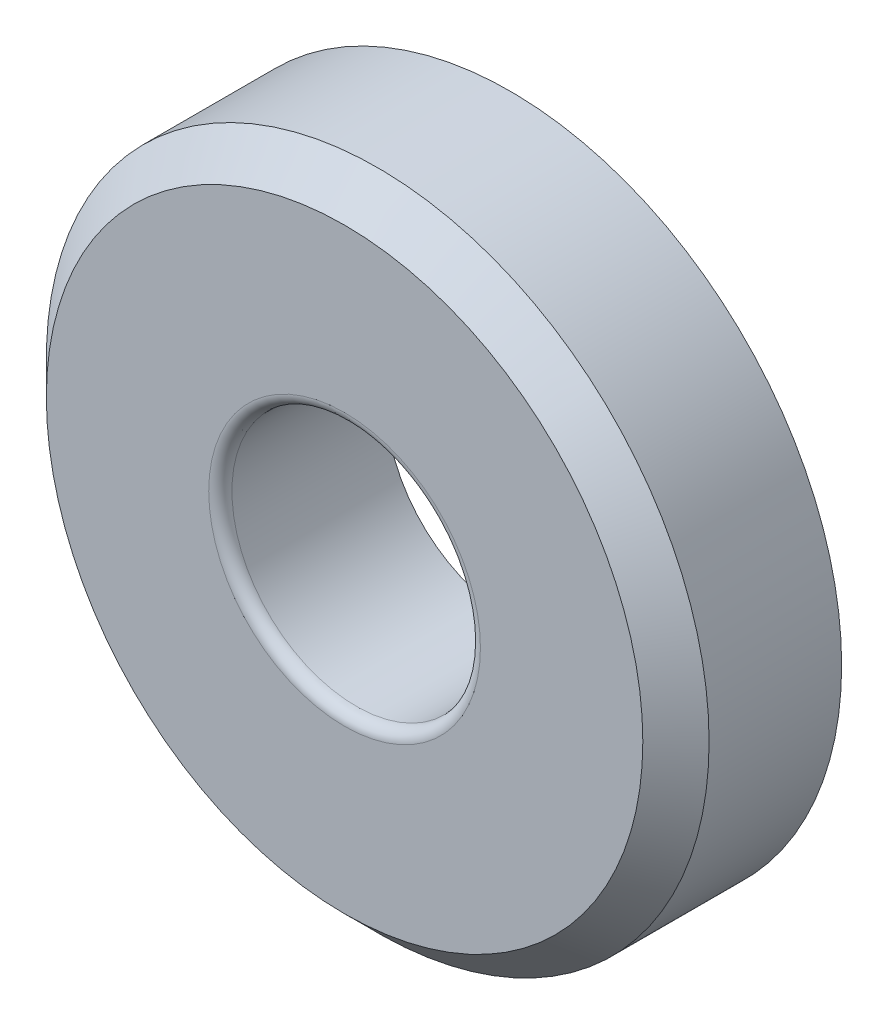
SolidWorks part; units mm, degrees
ref_plane "Front Plane" through (0, 0, 0) normal (0, 0, 1) x (1, 0, 0)
ref_plane "Top Plane" through (0, 0, 0) normal (0, 1, 0) x (1, 0, 0)
ref_plane "Right Plane" through (0, 0, 0) normal (1, 0, 0) x (0, 0, -1)
sketch "Sketch2" plane through (0, 0, 0) normal (0, 0, 1) x (1, 0, 0)
  circle A0 centre (0, 0) radius 25.4
  circle A1 centre (0, 0) radius 9.525
  dimension "D1" = 50.8
  dimension "D2" = 19.05
extrude "Boss-Extrude1" add sketch "Sketch2" along normal blind 12.7
chamfer "Chamfer1" distance 2.54 angle 45 1 edges at (25.4, 0, 12.7)
fillet "Fillet1" radius 0.889 1 edges at (9.525, 0, 12.7)
